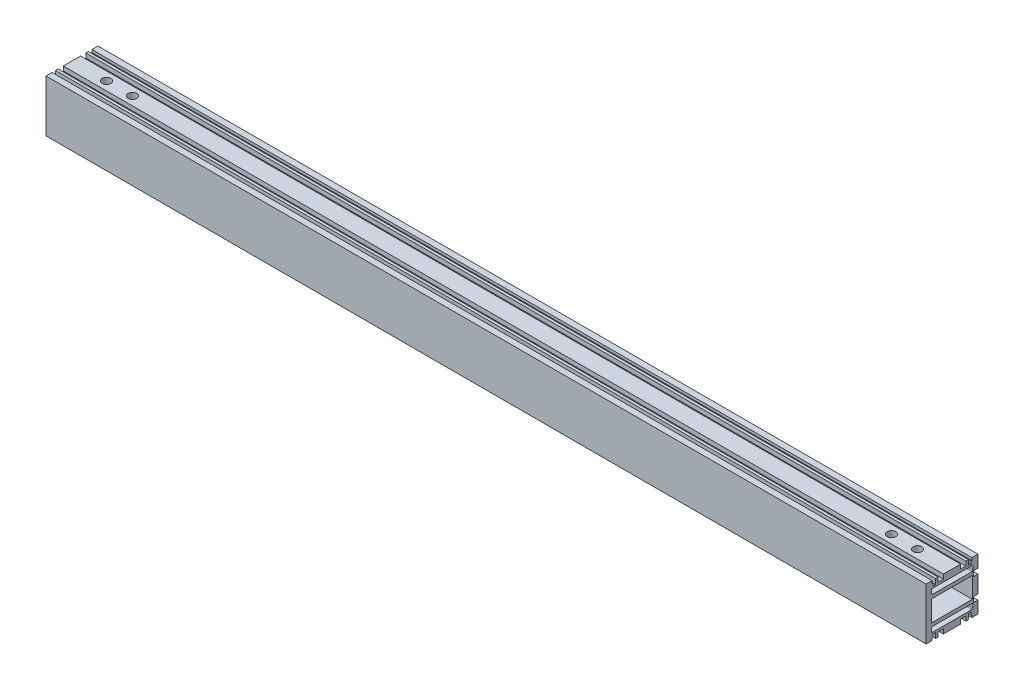
SolidWorks part; units mm, degrees
ref_plane "前视基准面" through (0, 0, 0) normal (0, 0, 1) x (1, 0, 0)
ref_plane "上视基准面" through (0, 0, 0) normal (0, 1, 0) x (1, 0, 0)
ref_plane "右视基准面" through (0, 0, 0) normal (1, 0, 0) x (0, 0, -1)
sketch "草图1" plane through (0, 0, 0) normal (1, 0, 0) x (0, 0, -1)
  line L0 (-15, 15) -> (15, -15) construction
  line L1 (-15, 15) -> (-11.5, 15)
  line L2 (-15, 15) -> (-15, -15)
  line L3 (-15, -15) -> (-11.5, -15)
  line L4 (15, 15) -> (15, 8)
  line L5 (15, 15) -> (-15, -15) construction
  line L6 (-11.5, 15) -> (-11.5, 13.5)
  line L7 (-11.5, 13.5) -> (-11, 13.5)
  line L8 (-11, 13.5) -> (-11, 12)
  line L9 (-11, 12) -> (-9.5, 12)
  line L10 (-9.5, 12) -> (-9.5, 15)
  line L11 (-9.5, 15) -> (-8, 15)
  line L12 (-8, 15) -> (-8, 12.5)
  line L13 (-8, 12.5) -> (-5, 12.5)
  line L14 (-5, 12.5) -> (-5, 15)
  line L15 (-5, 15) -> (5, 15)
  line L16 (0, 21.5201) -> (0, -18.309) construction
  line L17 (0, 55) -> (0, -55) construction
  line L18 (5, 12.5) -> (5, 15)
  line L19 (8, 12.5) -> (5, 12.5)
  line L20 (8, 15) -> (8, 12.5)
  line L21 (9.5, 15) -> (8, 15)
  line L22 (9.5, 12) -> (9.5, 15)
  line L23 (11, 12) -> (9.5, 12)
  line L24 (11, 13.5) -> (11, 12)
  line L25 (11.5, 13.5) -> (11, 13.5)
  line L26 (11.5, 15) -> (11.5, 13.5)
  line L27 (8, 15) -> (9.5, 15)
  line L28 (11.5, 15) -> (15, 15)
  line L29 (-19.8303, 0) -> (22.13, 0) construction
  line L30 (55, 0) -> (-55, 0) construction
  line L31 (8, -15) -> (9.5, -15)
  line L32 (11.5, -15) -> (11.5, -13.5)
  line L33 (11.5, -13.5) -> (11, -13.5)
  line L34 (11, -13.5) -> (11, -12)
  line L35 (11, -12) -> (9.5, -12)
  line L36 (9.5, -12) -> (9.5, -15)
  line L37 (9.5, -15) -> (8, -15)
  line L38 (8, -15) -> (8, -12.5)
  line L39 (8, -12.5) -> (5, -12.5)
  line L40 (5, -12.5) -> (5, -15)
  line L41 (-5, -15) -> (5, -15)
  line L42 (-5, -12.5) -> (-5, -15)
  line L43 (-8, -12.5) -> (-5, -12.5)
  line L44 (-8, -15) -> (-8, -12.5)
  line L45 (-9.5, -15) -> (-8, -15)
  line L46 (-9.5, -12) -> (-9.5, -15)
  line L47 (-11, -12) -> (-9.5, -12)
  line L48 (-11, -13.5) -> (-11, -12)
  line L49 (-11.5, -13.5) -> (-11, -13.5)
  line L50 (-11.5, -15) -> (-11.5, -13.5)
  line L51 (-9.5, -15) -> (-8, -15)
  line L52 (-5, -15) -> (5, -15)
  line L53 (8, -15) -> (9.5, -15)
  line L54 (11.5, -15) -> (15, -15)
  line L55 (15, 8) -> (12.5, 8)
  line L56 (12.5, 8) -> (12.5, 5)
  line L57 (12.5, 5) -> (15, 5)
  line L58 (12.5, -5) -> (15, -5)
  line L59 (12.5, -8) -> (12.5, -5)
  line L60 (15, -8) -> (12.5, -8)
  line L61 (15, 5) -> (15, -5)
  line L62 (15, -8) -> (15, -15)
  line L63 (12, -10.5) -> (12, -8.5)
  line L64 (-11.5, 11) -> (11.5, 11)
  line L65 (-12, 10.5) -> (-12, 8.5)
  line L66 (-11.5, 8) -> (11.5, 8)
  line L67 (12, 10.5) -> (12, 8.5)
  line L68 (-11.5, -8) -> (11.5, -8)
  line L69 (-12, -10.5) -> (-12, -8.5)
  line L70 (-11.5, -11) -> (11.5, -11)
  line L72 (-11.75, 6) -> (11.75, 6)
  line L73 (-11.75, 6) -> (-11.75, -6)
  line L74 (-11.75, -6) -> (11.75, -6)
  line L75 (11.75, 6) -> (11.75, -6)
  arc A0 (12, 8.5) -> (11.5, 8) centre (11.5, 8.5) cw
  arc A1 (11.5, 11) -> (12, 10.5) centre (11.5, 10.5) cw
  arc A2 (-11.5, 11) -> (-12, 10.5) centre (-11.5, 10.5) ccw
  arc A3 (-11.5, 8) -> (-12, 8.5) centre (-11.5, 8.5) cw
  arc A8 (-11.5, -8) -> (-12, -8.5) centre (-11.5, -8.5) ccw
  arc A9 (-11.5, -11) -> (-12, -10.5) centre (-11.5, -10.5) cw
  arc A10 (11.5, -11) -> (12, -10.5) centre (11.5, -10.5) ccw
  arc A11 (12, -8.5) -> (11.5, -8) centre (11.5, -8.5) ccw
  point P69 (12, 11)
  point P72 (-12, 11)
  point P77 (-11, -13.5)
  point P80 (11, -13.5)
  point P83 (11, 13.5)
  point P86 (-11, 13.5)
  point P99 (-12, -11)
  point P100 (12, -11)
  dimension "D17" = 0.5
  dimension "D1" = 3.5
  dimension "D2" = 1.5
  dimension "D3" = 0.5
  dimension "D4" = 1.5
  dimension "D5" = 3
  dimension "D6" = 30
  dimension "D7" = 30
  dimension "D8" = 1.5
  dimension "D9" = 2.5
  dimension "D10" = 3
  dimension "D11" = 2.5
  dimension "D12" = 7
  dimension "D13" = 3
  dimension "D14" = 4
  dimension "D15" = 3
  dimension "D16" = 24
  dimension "D19" = 23.5
  dimension "D20" = 12
extrude "凸台-拉伸1" add sketch "草图1" along normal mid plane 509
hole_wizard "M6 螺纹孔1" positions "草图3" profile "草图2" tap size "M6" standard "GB"
sketch "草图3" plane through (0, 0, -15) normal (0, 0, -1) x (-1, 0, 0)
  point P0 (-234.5, 0)
  point P3 (-219.5, 0)
  point P6 (1.5, 0)
  point P9 (16.5, 0)
sketch "草图2" plane through (234.5, 0, -15) normal (1, 0, 0) x (0, 1, 0)
  line L0 (0, 0) -> (0, 20.5022)
  line L1 (0, 20.5022) -> (2.5, 19)
  line L2 (2.5, 19) -> (2.5, 0)
  line L5 (2.5, 0) -> (0, 0)
  line L10 (0, 20.5022) -> (-2.5, 19) construction
  line L11 (0, -6.35) -> (0, 107.95) construction
  dimension "螺纹孔钻头直径" = 5
  dimension "螺纹孔钻头深度" = 19
  dimension "导头角度" = 118
cosmetic thread "孔螺蚊线1" parameters "D1"=3.25, "D2"=6
cosmetic thread "孔螺蚊线2" parameters "D1"=3.25, "D2"=6
cosmetic thread "孔螺蚊线3" parameters "D1"=3.25, "D2"=6
cosmetic thread "孔螺蚊线4" parameters "D1"=3.25, "D2"=6
hole_wizard "M6 螺纹孔2" positions "草图5" profile "草图4" tap size "M6" standard "GB"
sketch "草图5" plane through (0, 15, 0) normal (0, 1, 0) x (1, 0, 0)
  point P0 (234.5, 0)
  point P3 (219.5, 0)
  point P6 (-219.5, 0)
  point P9 (-234.5, 0)
sketch "草图4" plane through (234.5, 15, 0) normal (1, 0, 0) x (0, 0, 1)
  line L0 (0, 0) -> (0, 20.5022)
  line L1 (0, 20.5022) -> (2.5, 19)
  line L2 (2.5, 19) -> (2.5, 0)
  line L5 (2.5, 0) -> (0, 0)
  line L10 (0, 20.5022) -> (-2.5, 19) construction
  line L11 (0, -6.35) -> (0, 107.95) construction
  dimension "螺纹孔钻头直径" = 5
  dimension "螺纹孔钻头深度" = 19
  dimension "导头角度" = 118
cosmetic thread "孔螺蚊线5" parameters "D1"=9, "D2"=6
cosmetic thread "孔螺蚊线6" parameters "D1"=9, "D2"=6
cosmetic thread "孔螺蚊线7" parameters "D1"=9, "D2"=6
cosmetic thread "孔螺蚊线8" parameters "D1"=9, "D2"=6
